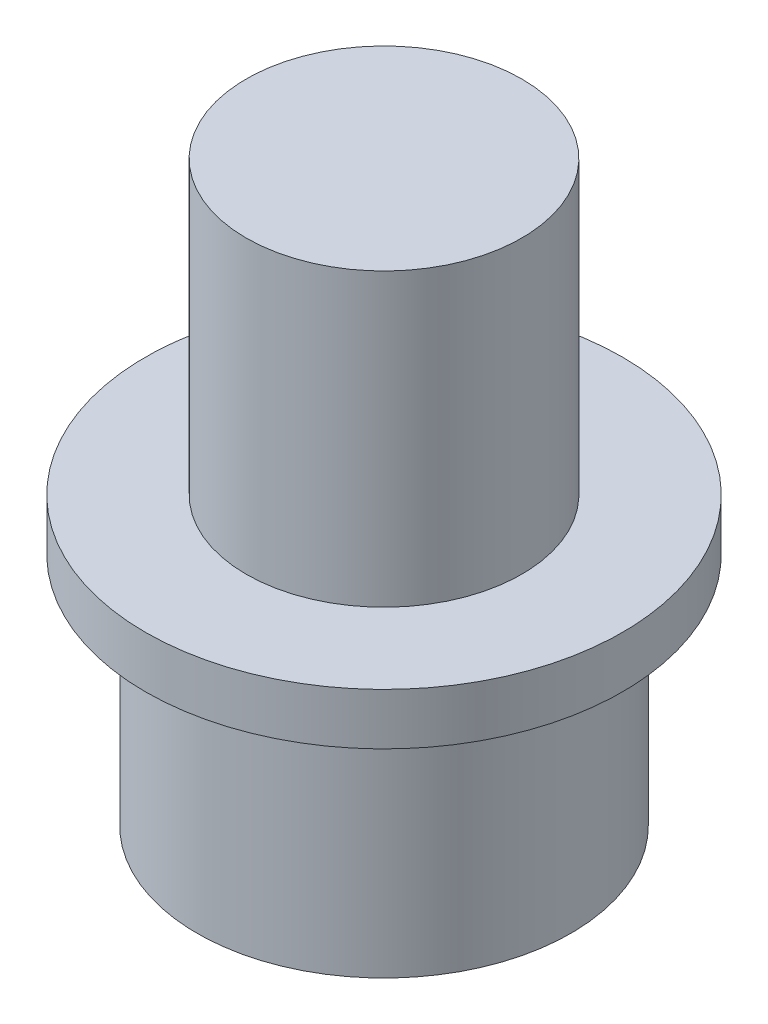
SolidWorks part; units mm, degrees
material "黄铜"
ref_plane "前视基准面" through (0, 0, 0) normal (0, 0, 1) x (1, 0, 0)
ref_plane "上视基准面" through (0, 0, 0) normal (0, 1, 0) x (1, 0, 0)
ref_plane "右视基准面" through (0, 0, 0) normal (1, 0, 0) x (0, 0, -1)
sketch "草图1" plane through (0, 0, 0) normal (0, 0, 1) x (1, 0, 0)
  line L0 (0, 0) -> (0, 22.7151) construction
  line L1 (0, 0) -> (0, 9.64)
  line L2 (0, 9.64) -> (2.3, 9.64)
  line L3 (2.3, 9.64) -> (2.3, 5.4)
  line L4 (2.3, 5.4) -> (3.98, 5.4)
  line L5 (3.98, 5.4) -> (3.98, 3.92)
  line L6 (3.98, 3.92) -> (3.12, 3.92)
  line L7 (3.12, 3.92) -> (3.12, 0)
  line L8 (3.12, 0) -> (0, 0)
  dimension "D1" = 9.64
  dimension "D2" = 5.4
  dimension "D3" = 1.48
  dimension "D4" = 2.3
  dimension "D5" = 3.98
  dimension "D6" = 3.12
revolve "旋转1" add sketch "草图1" angle 360 about L0
cosmetic thread "装饰螺纹线1" parameters "D2"=3.242
sketch "草图2" plane through (0, 0, 0) normal (0, -1, 0) x (1, 0, 0)
  circle A0 centre (0, 0) radius 2.3
  dimension "D1" = 4.6
extrude "切除-拉伸1" cut sketch "草图2" against normal blind 3.92
cosmetic thread "装饰螺纹线2" parameters "D1"=3.92, "D2"=6
sketch "草图3" plane through (0, 5.4, 0) normal (0, 1, 0) x (1, 0, 0)
  circle A1 centre (0, 0) radius 3.98
  circle A2 centre (0, 0) radius 3.98
  circle M2 centre (0, 0) radius 2.3
  circle M3 centre (0, 0) radius 3.98
  dimension "D1" = 0
extrude "切除-拉伸2" cut sketch "草图3" against normal blind 0.62 contours M3 M2
